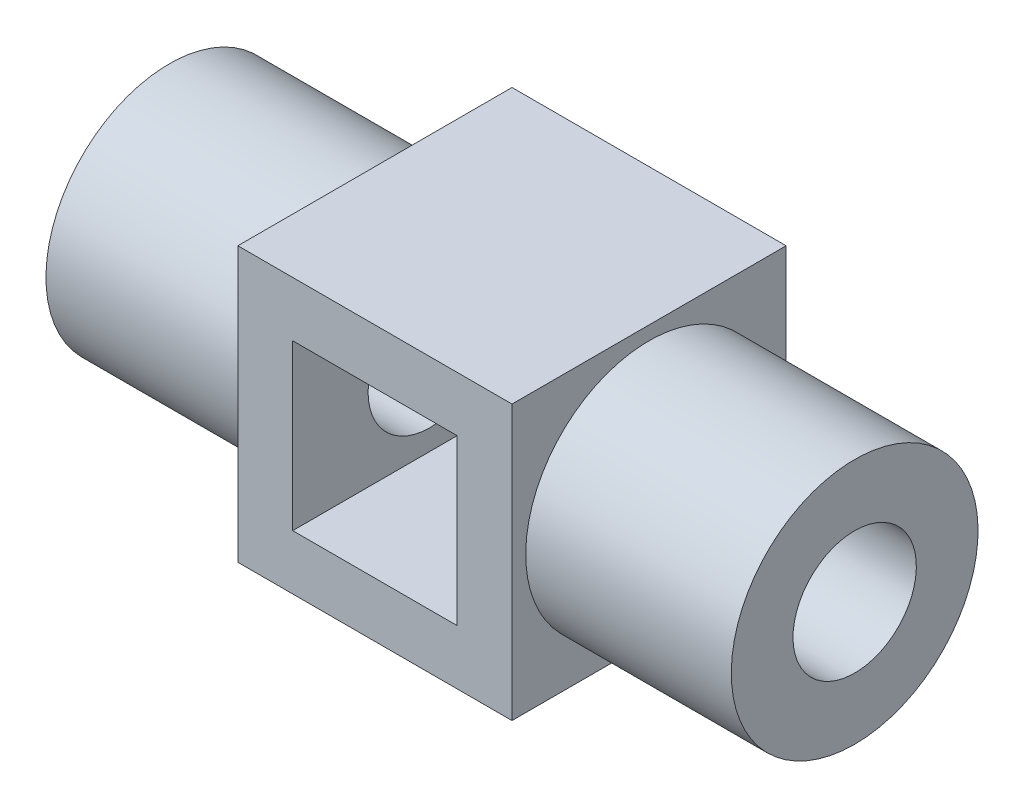
SolidWorks part; units mm, degrees
ref_plane "Front Plane" through (0, 0, 0) normal (0, 0, 1) x (1, 0, 0)
ref_plane "Top Plane" through (0, 0, 0) normal (0, 1, 0) x (1, 0, 0)
ref_plane "Right Plane" through (0, 0, 0) normal (1, 0, 0) x (0, 0, -1)
sketch "Sketch1" plane through (0, 0, 0) normal (0, 0, 1) x (1, 0, 0)
  line L1 (-20, 20) -> (20, 20)
  line L2 (-20, 20) -> (-20, -20)
  line L3 (-20, -20) -> (20, -20)
  line L4 (20, 20) -> (20, -20)
  line L5 (-20, 20) -> (20, -20) construction
  line L6 (-20, -20) -> (20, 20) construction
  line L7 (-12, 12) -> (12, 12)
  line L8 (-12, 12) -> (-12, -12)
  line L9 (-12, -12) -> (12, -12)
  line L10 (12, 12) -> (12, -12)
  line L11 (-12, 12) -> (12, -12) construction
  line L12 (-12, -12) -> (12, 12) construction
  point P0 (0, 0)
  point P6 (0, 0)
  dimension "D1" = 40
  dimension "D2" = 24
extrude "Boss-Extrude1" add sketch "Sketch1" along normal blind 40
sketch "Sketch2" plane through (-20, 0, 0) normal (-1, 0, 0) x (0, 0, 1)
  circle A0 centre (20, 0) radius 18
extrude "Boss-Extrude3" add sketch "Sketch2" along normal blind 30
sketch "Sketch3" plane through (-50, 0, 0) normal (-1, 0, 0) x (0, 0, 1)
  circle A0 centre (20, 0) radius 9
extrude "Cut-Extrude1" cut sketch "Sketch3" against normal up to surface (62 mm away)
mirror "Mirror1" about plane through (0, 0, 0) normal (1, 0, 0) of "Cut-Extrude1", "Boss-Extrude3"
